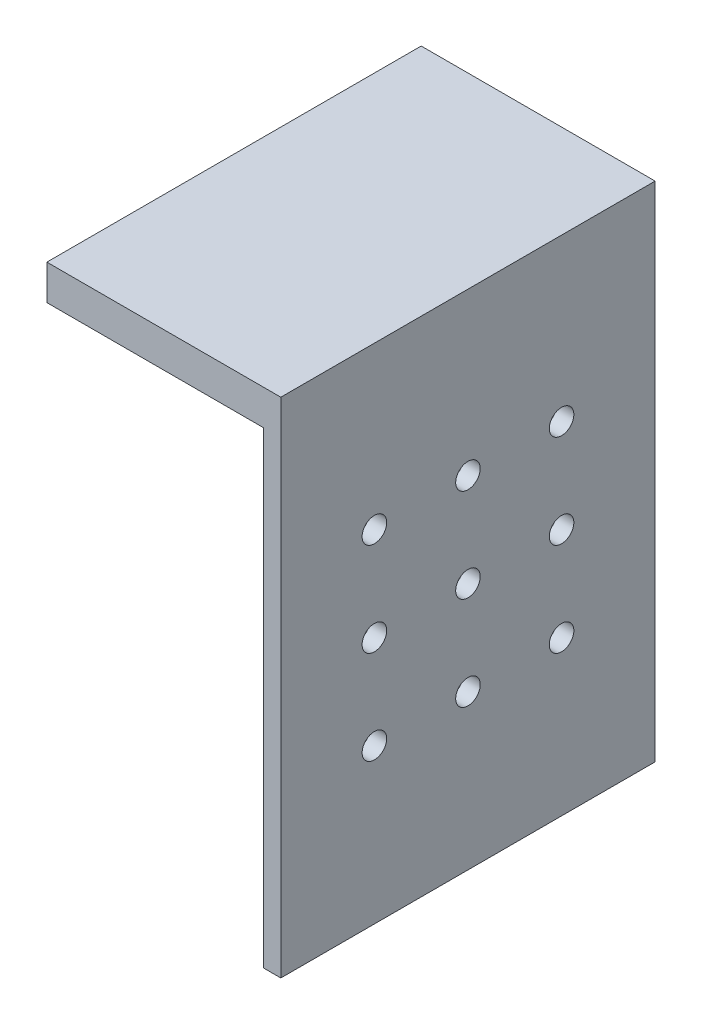
SolidWorks part; units mm, degrees
ref_plane "前视基准面" through (0, 0, 0) normal (0, 0, 1) x (1, 0, 0)
ref_plane "上视基准面" through (0, 0, 0) normal (0, 1, 0) x (1, 0, 0)
ref_plane "右视基准面" through (0, 0, 0) normal (1, 0, 0) x (0, 0, -1)
sketch "草图1" plane through (0, 0, 0) normal (0, 0, 1) x (1, 0, 0)
  line L1 (0, 0) -> (15, 0)
  line L2 (0, 0) -> (0, 40)
  line L3 (0, 40) -> (15, 40)
  line L4 (15, 0) -> (15, 40)
extrude "凸台-拉伸1" add sketch "草图1" along normal blind 32
sketch "草图3" plane through (0, 40, 0) normal (0, 1, 0) x (1, 0, 0)
  line L1 (0, 0) -> (15, 0)
  line L2 (0, 0) -> (0, -32)
  line L3 (0, -32) -> (15, -32)
  line L4 (15, 0) -> (15, -32)
extrude "凸台-拉伸2" add sketch "草图3" along normal blind 10
sketch "草图5" plane through (0, 0, 32) normal (0, 0, 1) x (1, 0, 0)
  line L0 (0, 0) -> (13, 0)
  line L1 (0, 0) -> (15, 0) construction
  line L2 (13, 0) -> (13, 45)
  line L3 (13, 45) -> (0, 45)
  line L4 (0, 50) -> (0, 0) construction
  line L5 (0, 45) -> (0, 0)
extrude "切除-拉伸1" cut sketch "草图5" against normal through all
sketch "草图7" plane through (15, 0, 0) normal (1, 0, 0) x (0, 0, -1)
  line L1 (-32, 50) -> (0, 50)
  line L2 (-32, 50) -> (-32, 0)
  line L3 (-32, 0) -> (0, 0)
  line L4 (0, 50) -> (0, 0)
extrude "凸台-拉伸3" add sketch "草图7" along normal blind 5
sketch "草图8" plane through (0, 0, 32) normal (0, 0, 1) x (1, 0, 0)
  line L1 (13, 45) -> (16, 45)
  line L2 (13, 45) -> (13, 5)
  line L3 (13, 5) -> (16, 5)
  line L4 (16, 45) -> (16, 5)
extrude "切除-拉伸2" cut sketch "草图8" against normal through all
sketch "草图9" plane through (0, 0, 32) normal (0, 0, 1) x (1, 0, 0)
  line L0 (13, 0) -> (20, 0) construction
  line L1 (13, 5) -> (16, 5)
  line L2 (13, 5) -> (13, 0)
  line L3 (13, 0) -> (16, 0)
  line L4 (16, 5) -> (16, 0)
extrude "切除-拉伸3" cut sketch "草图9" against normal through all
sketch "草图10" plane through (0, 45, 0) normal (0, -1, 0) x (1, 0, 0)
  circle A0 centre (3, 16) radius 1.5
extrude "凸台-拉伸4" add sketch "草图10" along normal blind 5
sketch "草图11" plane through (20, 0, 0) normal (1, 0, 0) x (0, 0, -1)
  circle A0 centre (-24, 34.2) radius 1.05
  circle A1 centre (-24, 26.2) radius 1.05
  circle A2 centre (-24, 18.2) radius 1.05
  circle A3 centre (-16, 34.2) radius 1.05
  circle A4 centre (-16, 26.2) radius 1.05
  circle A5 centre (-16, 18.2) radius 1.05
  circle A6 centre (-8, 18.2) radius 1.05
  circle A7 centre (-8, 26.2) radius 1.05
  circle A8 centre (-8, 34.2) radius 1.05
extrude "切除-拉伸4" cut sketch "草图11" against normal through all
sketch "草图12" plane through (0, 0, 32) normal (0, 0, 1) x (1, 0, 0)
  line L0 (20, 50) -> (20, 0) construction
  line L1 (16, 0) -> (20, 0)
  line L2 (16, 0) -> (16, 5)
  line L3 (16, 5) -> (20, 5)
  line L4 (20, 0) -> (20, 5)
extrude "切除-拉伸5" cut sketch "草图12" against normal through all
sketch "草图13" plane through (0, 0, 32) normal (0, 0, 1) x (1, 0, 0)
  line L0 (20, 5) -> (16, 5) construction
  line L1 (16, 45) -> (18.5381, 45)
  line L2 (16, 45) -> (16, 5)
  line L3 (16, 5) -> (18.5381, 5)
  line L4 (18.5381, 45) -> (18.5381, 5)
extrude "切除-拉伸6" cut sketch "草图13" against normal through all
sketch "草图14" plane through (0, 0, 32) normal (0, 0, 1) x (1, 0, 0)
  line L0 (20, 50) -> (20, 5) construction
  line L1 (0, 50) -> (20, 50)
  line L2 (0, 50) -> (0, 48)
  line L3 (0, 48) -> (20, 48)
  line L4 (20, 50) -> (20, 48)
extrude "切除-拉伸7" cut sketch "草图14" against normal through all
